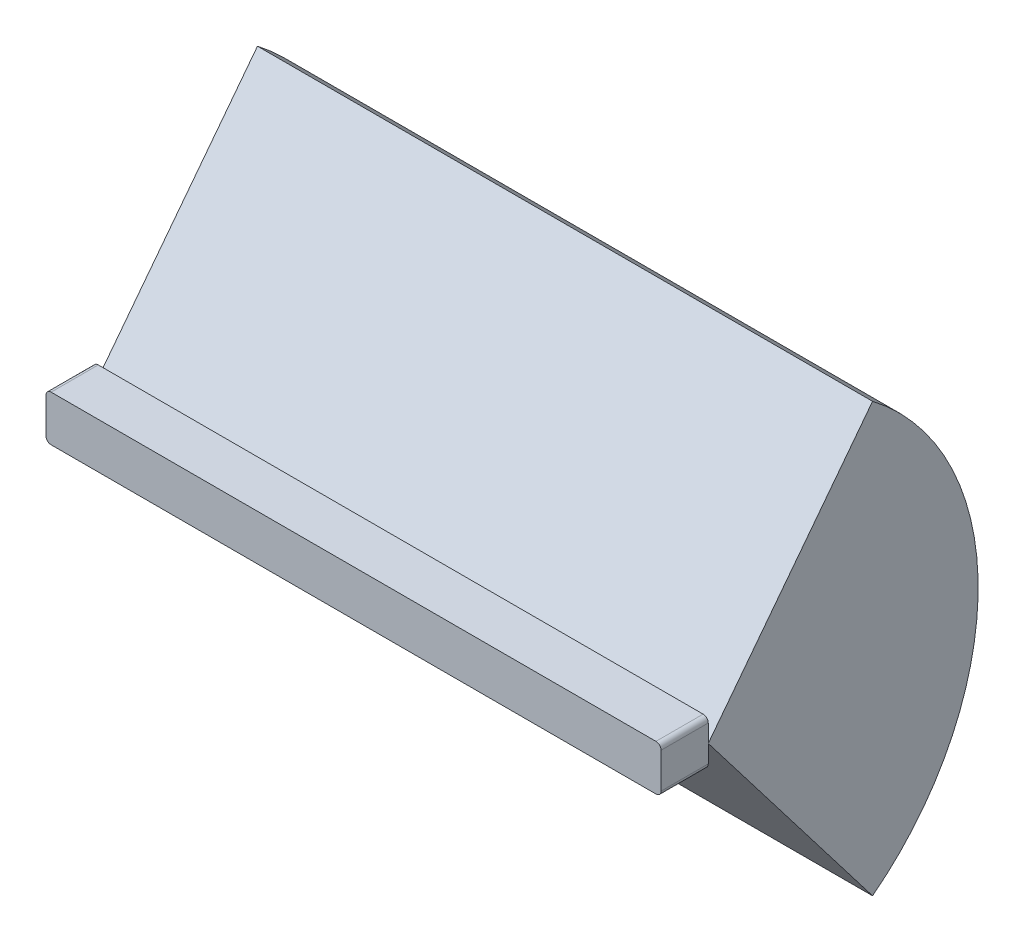
SolidWorks part; units mm, degrees
ref_plane "Plan de face" through (0, 0, 0) normal (0, 0, 1) x (1, 0, 0)
ref_plane "Plan de dessus" through (0, 0, 0) normal (0, 1, 0) x (1, 0, 0)
ref_plane "Plan de droite" through (0, 0, 0) normal (1, 0, 0) x (0, 0, -1)
sketch "Esquisse1" plane through (0, 0, 0) normal (0, 0, 1) x (1, 0, 0)
  line L1 (-590, -44.5) -> (590, -44.5)
  line L2 (-600, -34.5) -> (-600, 34.5)
  line L3 (-590, 44.5) -> (590, 44.5)
  line L4 (600, -34.5) -> (600, 34.5)
  line L5 (-600, -44.5) -> (600, 44.5) construction
  line L6 (-600, 44.5) -> (600, -44.5) construction
  arc A0 (-590, -44.5) -> (-600, -34.5) centre (-590, -34.5) cw
  arc A1 (-600, 34.5) -> (-590, 44.5) centre (-590, 34.5) cw
  arc A2 (590, -44.5) -> (600, -34.5) centre (590, -34.5) ccw
  arc A3 (600, 34.5) -> (590, 44.5) centre (590, 34.5) ccw
  point P0 (0, 0)
  dimension "D3" = 10
  dimension "D1" = 1200
  dimension "D2" = 89
extrude "Boss.-Extru.1" add sketch "Esquisse1" along normal blind 92
sketch "Esquisse3" plane through (600, 0, 0) normal (1, 0, 0) x (0, 0, -1)
  line L0 (0, 0) -> (-617.9558, 0) construction
  line L1 (0, -34.5) -> (0, 34.5) construction
  line L2 (0, 0) -> (320.5442, 417.7414)
  line L3 (0, 0) -> (320.5442, -417.7414)
  line L4 (0, 0) -> (351.8183, 0) construction
  arc A0 (320.5442, -417.7414) -> (320.5442, 417.7414) centre (0, 0) ccw
  dimension "D1" = 105
  dimension "D2" = 52.5
extrude "Boss.-Extru.2" add sketch "Esquisse3" against normal through all separate body
